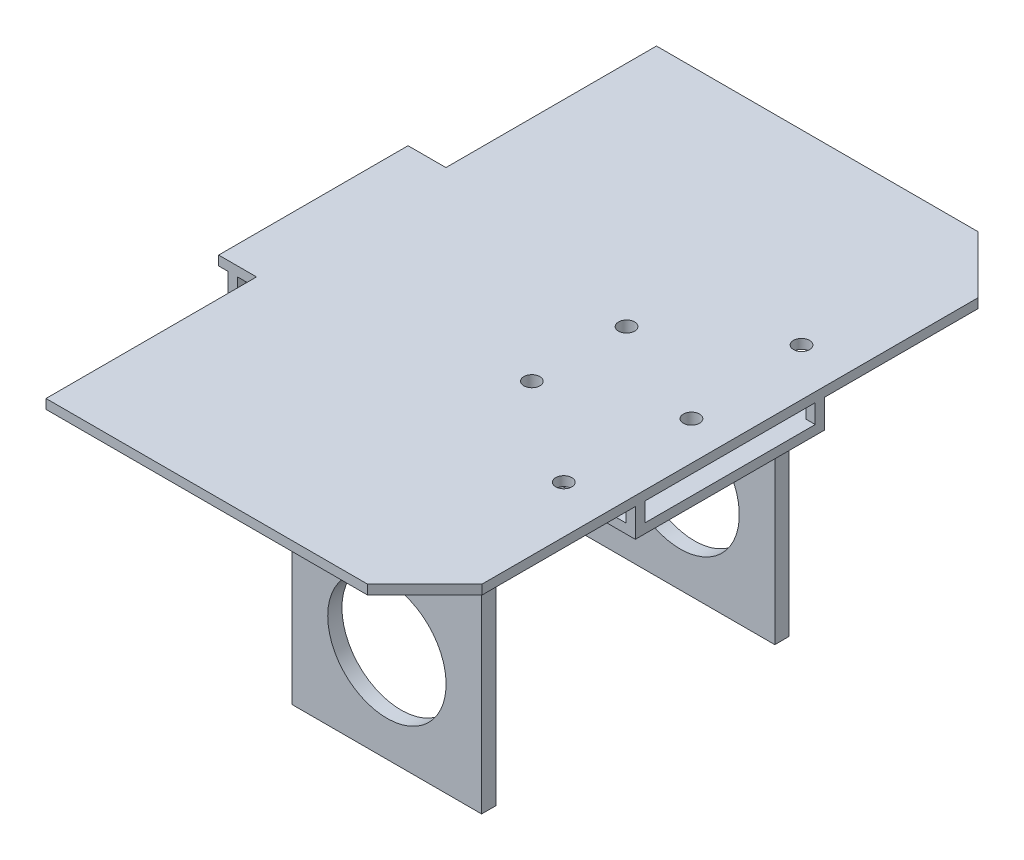
SolidWorks part; units mm, degrees
ref_plane "Front Plane" through (0, 0, 0) normal (0, 0, 1) x (1, 0, 0)
ref_plane "Top Plane" through (0, 0, 0) normal (0, 1, 0) x (1, 0, 0)
ref_plane "Right Plane" through (0, 0, 0) normal (1, 0, 0) x (0, 0, -1)
sketch "Sketch1" plane through (0, 0, 0) normal (0, 1, 0) x (1, 0, 0)
  line L1 (0, 0) -> (40, 0)
  line L2 (0, 0) -> (0, 40)
  line L3 (0, 40) -> (40, 40)
  line L4 (40, 0) -> (40, 40)
  dimension "D1" = 40
  dimension "D2" = 40
extrude "Boss-Extrude1" add sketch "Sketch1" along normal blind 2
sketch "Sketch10" plane through (0, 2, 0) normal (0, 1, 0) x (1, 0, 0)
  line L0 (40, 0) -> (40, 40) construction
  line L1 (0, 0) -> (40, 0)
  line L2 (0, 0) -> (0, 2)
  line L3 (0, 2) -> (40, 2)
  line L4 (40, 0) -> (40, 2)
  line L6 (0, 40) -> (40, 40)
  line L7 (0, 40) -> (0, 38)
  line L8 (0, 38) -> (40, 38)
  line L9 (40, 40) -> (40, 38)
  dimension "D1" = 2
extrude "Boss-Extrude4" add sketch "Sketch10" along normal blind 4
sketch "Sketch11" plane through (0, 6, 0) normal (0, 1, 0) x (1, 0, 0)
  line L1 (0, 40) -> (40, 40)
  line L2 (0, 40) -> (0, 0)
  line L3 (0, 0) -> (40, 0)
  line L4 (40, 40) -> (40, 0)
extrude "Boss-Extrude5" add sketch "Sketch11" along normal blind 2
hole_wizard "M3 Clearance Hole1" positions "Sketch3" profile "Sketch4" hole size "M3" standard "ANSI Metric" end condition through all
sketch "Sketch3" plane through (0, 0, 0) normal (0, 1, 0) x (1, 0, 0)
  line L0 (8.15, 30) -> (8.15, 40) construction
  line L1 (40, 40) -> (0, 40) construction
  line L3 (8.15, 10) -> (8.15, 0) construction
  line L4 (0, 0) -> (40, 0) construction
  line L7 (8.15, 30) -> (0, 30) construction
  line L8 (0, 38) -> (0, 2) construction
  line L10 (31.85, 20) -> (40, 20) construction
  line L11 (40, 2) -> (40, 38) construction
  point P0 (8.15, 30)
  point P2 (8.15, 10)
  point P23 (31.85, 20)
  dimension "D1" = 20
  dimension "D3" = 23.7
sketch "Sketch4" plane through (8.15, 0, -30) normal (1, 0, 0) x (0, 0, -1)
  line L0 (0, 0) -> (0, 8)
  line L1 (0, 8) -> (1.7, 8)
  line L2 (1.7, 8) -> (1.7, 0)
  line L5 (1.7, 0) -> (0, 0)
  line L11 (0, -6.35) -> (0, 107.95) construction
  dimension "Thru Hole Dia." = 3.4
  dimension "Thru Hole Depth" = 8
sketch "Sketch5" plane through (0, 0, 0) normal (1, 0, 0) x (0, 0, -1)
  line L0 (0, 8) -> (0, 6)
  line L1 (0, 8) -> (0, 0) construction
  line L2 (0, 6) -> (40, 6)
  line L3 (40, 8) -> (40, 0) construction
  line L4 (0, 0) -> (40, 0)
  line L5 (40, 0) -> (40, 8)
  line L6 (40, 8) -> (0, 8)
  line L7 (0, 8) -> (0, 0)
  line L12 (40, 8) -> (0, 8)
  line L13 (40, 6) -> (40, 8)
  line L14 (2, 6) -> (38, 6) construction
  dimension "D1" = 0
extrude "Boss-Extrude2" add sketch "Sketch5" against normal blind 48
sketch "Sketch6" plane through (-6, 6, 0) normal (0, 1, 0) x (-1, 0, 0)
  line L1 (40, -40) -> (38, -40)
  line L2 (40, -40) -> (40, 0)
  line L3 (40, 0) -> (38, 0)
  line L4 (38, -40) -> (38, 0)
  line L6 (-46, -40) -> (42, -40) construction
  line L7 (42, 0) -> (-46, 0) construction
  line L8 (42, -40) -> (42, 0) construction
  dimension "D1" = 2
  dimension "D2" = 2
extrude "Boss-Extrude3" add sketch "Sketch6" against normal blind 6
sketch "Sketch7" plane through (46, 0, 0) normal (0, 1, 0) x (-1, 0, 0)
  line L0 (90, 0) -> (90, -40) construction
  line L1 (90, -6) -> (92, -6)
  line L2 (90, -6) -> (90, -34)
  line L3 (90, -34) -> (92, -34)
  line L4 (92, -6) -> (92, -34)
  line L5 (92, -40) -> (92, 0) construction
  line L6 (90, -40) -> (92, -40) construction
  line L7 (92, 0) -> (90, 0) construction
  dimension "D1" = 6
  dimension "D2" = 6
extrude "Cut-Extrude1" cut sketch "Sketch7" along normal up to surface (6 mm away) up to face at (-47, 6, -20)
hole_wizard "M3 Clearance Hole2" positions "Sketch8" profile "Sketch9" hole size "M3" standard "ANSI Metric"
sketch "Sketch8" plane through (-46, 0, 0) normal (-1, 0, 0) x (0, 0, -1)
  line L7 (0, 0) -> (6, -6) construction
  line L8 (6, -6) -> (0, -6) construction
  line L10 (34, 0) -> (40, -6) construction
  point P0 (3, -3)
  point P2 (37, -3)
sketch "Sketch9" plane through (-46, 3, -3) normal (0, 1, 0) x (0, 0, 1)
  line L0 (0, 0) -> (0, 3.0215)
  line L1 (0, 3.0215) -> (1.7, 2)
  line L2 (1.7, 2) -> (1.7, 0)
  line L5 (1.7, 0) -> (0, 0)
  line L10 (0, 3.0215) -> (-1.7, 2) construction
  line L11 (0, -6.35) -> (0, 107.95) construction
  dimension "Hole Dia." = 3.4
  dimension "Hole Depth" = 2
  dimension "Drill Angle" = 118
sketch "Sketch12" plane through (0, 0, -40) normal (0, 0, -1) x (-1, 0, 0)
  line L0 (-40, 8) -> (-40, 0) construction
  line L1 (-38, 6) -> (-2, 6)
  line L2 (-38, 6) -> (-38, 2)
  line L3 (-38, 2) -> (-2, 2)
  line L4 (-2, 6) -> (-2, 2)
  line L5 (-40, 6) -> (0, 6) construction
  line L6 (-40, 6) -> (0, 6)
  line L7 (-40, 2) -> (0, 2) construction
  line L8 (-40, 2) -> (0, 2)
  line L9 (0, 6) -> (0, 0) construction
  dimension "D1" = 2
  dimension "D2" = 2
extrude "Cut-Extrude2" cut sketch "Sketch12" against normal through all contours L4 L1 L2 L3
sketch "Sketch13" plane through (0, 2, 0) normal (0, 1, 0) x (1, 0, 0)
  circle A0 centre (31.85, 20) radius 1.7 construction
  circle A1 centre (8.15, 10) radius 1.7 construction
  circle A2 centre (8.15, 30) radius 1.7 construction
  circle A3 centre (31.85, 20) radius 1.7
  circle A4 centre (8.15, 10) radius 1.7
  circle A5 centre (8.15, 30) radius 1.7
extrude "Extrude-Thin1" add sketch "Sketch13" along normal up to next thin
sketch "Sketch14" plane through (0, 0, -40) normal (0, 0, -1) x (-1, 0, 0)
  line L2 (-40, 8) -> (0, 8)
  line L3 (-40, 8) -> (-40, 6)
  line L4 (-40, 6) -> (0, 6)
  line L5 (0, 8) -> (0, 6)
extrude "Boss-Extrude6" add sketch "Sketch14" along normal up to surface (44.465 mm away)
hole_wizard "M3 Clearance Hole3" positions "Sketch15" profile "Sketch17" hole size "M3" standard "ANSI Metric" end condition through all
sketch "Sketch15" plane through (0, 8, 0) normal (0, 1, 0) x (1, 0, 0)
  line L1 (40, 0) -> (40, 84.465) construction
  point P2 (30, 45.1056)
  dimension "D2" = 10
sketch "Sketch17" plane through (30, 8, -45.1056) normal (1, 0, 0) x (0, 0, 1)
  line L0 (0, 0) -> (0, 8)
  line L1 (0, 8) -> (1.7, 8)
  line L2 (1.7, 8) -> (1.7, 0)
  line L5 (1.7, 0) -> (0, 0)
  line L11 (0, -6.35) -> (0, 107.95) construction
  dimension "Thru Hole Dia." = 3.4
  dimension "Thru Hole Depth" = 8
sketch "Sketch19" plane through (0, 0, 0) normal (0, 0, 1) x (1, 0, 0)
  line L1 (40, 8) -> (0, 8)
  line L2 (40, 8) -> (40, 6)
  line L3 (40, 6) -> (0, 6)
  line L4 (0, 8) -> (0, 6)
extrude "Boss-Extrude7" add sketch "Sketch19" along normal up to surface (44.465 mm away)
sketch "Sketch20" plane through (0, 8, 0) normal (0, 1, 0) x (1, 0, 0)
  line L0 (-48, 20) -> (40, 20) construction
  line L1 (-48, 40) -> (-48, 0) construction
  line L2 (40, -44.465) -> (40, 84.465) construction
  circle A0 centre (30, 45.1056) radius 1.7 construction
  circle A2 centre (30, 45.1056) radius 1.7 construction
  circle A4 centre (30, -5.1056) radius 1.7
extrude "Cut-Extrude3" cut sketch "Sketch20" against normal through all
sketch "Sketch21" plane through (0, 8, 0) normal (0, 1, 0) x (1, 0, 0)
  line L0 (27.91, -44.465) -> (40, -32.375)
  line L1 (27.91, -44.465) -> (40, -32.375) construction
  line L2 (0, -44.465) -> (40, -44.465) construction
  line L3 (40, -44.465) -> (40, 84.465) construction
  line L4 (40, -32.375) -> (40, -44.465)
  line L5 (40, -44.465) -> (27.91, -44.465)
  line L6 (27.91, 84.465) -> (40, 84.465)
  line L7 (40, 84.465) -> (0, 84.465) construction
  line L8 (40, 84.465) -> (40, 72.375)
  line L9 (40, 72.375) -> (27.91, 84.465)
  line L10 (40, 72.375) -> (27.91, 84.465) construction
  point P17 (40, 72.375)
  point P21 (27.91, 84.465)
  point P22 (27.91, 84.465)
extrude "Cut-Extrude4" cut sketch "Sketch21" against normal through all
sketch "Sketch24" plane through (0, 0, 0) normal (-1, 0, 0) x (0, 0, 1)
  line L0 (-84.465, 6) -> (-40, 6) construction
  line L1 (-84.465, 8) -> (-40, 8)
  line L2 (-84.465, 8) -> (-84.465, 6)
  line L3 (-84.465, 6) -> (-40, 6)
  line L4 (-40, 8) -> (-40, 6)
extrude "Boss-Extrude9" add sketch "Sketch24" along normal blind 40
sketch "Sketch22" plane through (0, 6, 0) normal (0, -1, 0) x (1, 0, 0)
  line L0 (27.91, -84.465) -> (-40, -84.465) construction
  line L1 (20, -49.465) -> (-20, -49.465)
  line L2 (20, -49.465) -> (20, -52.465)
  line L3 (20, -52.465) -> (-20, -52.465)
  line L4 (-20, -49.465) -> (-20, -52.465)
  line L5 (40, 32.375) -> (40, -72.375) construction
  dimension "D1" = 40
  dimension "D2" = 35
  dimension "D3" = 20
  dimension "D4" = 3
extrude "Boss-Extrude8" add sketch "Sketch22" along normal blind 60
fillet "Fillet1" radius 2 4 edges at (0, 6, -49.465) (20, 6, -50.965) (0, 6, -52.465) (-20, 6, -50.965)
ref_plane "Plane1" through (0, 0, -20) normal (0, 0, -1) x (-1, 0, 0)
sketch "Sketch23" plane through (0, 0, -52.465) normal (0, 0, -1) x (-1, 0, 0)
  line L0 (0, -34) -> (0, -54) construction
  line L3 (20, -54) -> (-20, -54) construction
  circle A0 centre (0, -34) radius 12.5
  dimension "D1" = 25
  dimension "D2" = 20
extrude "Cut-Extrude5" cut sketch "Sketch23" against normal up to next
mirror "Mirror1" about plane through (0, 0, -20) normal (0, 0, -1) of "Boss-Extrude9", "Boss-Extrude8", "Fillet1", "Cut-Extrude5"
